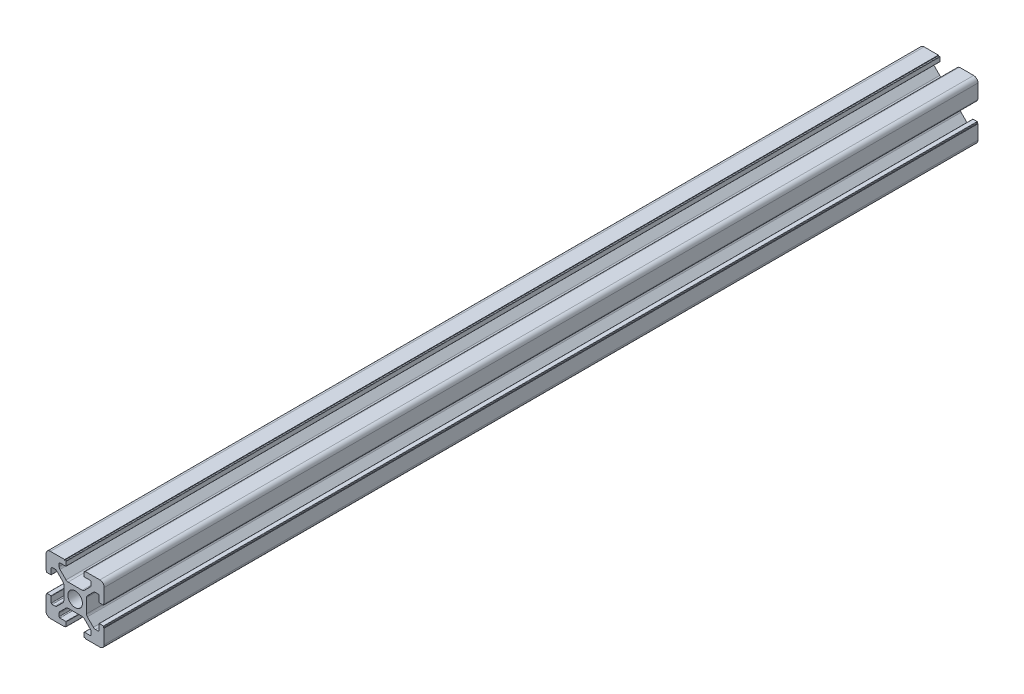
SolidWorks part; units mm, degrees
material "6063-T5"
ref_plane "前视基准面" through (0, 0, 0) normal (0, 0, 1) x (1, 0, 0)
ref_plane "上视基准面" through (0, 0, 0) normal (0, 1, 0) x (1, 0, 0)
ref_plane "右视基准面" through (0, 0, 0) normal (1, 0, 0) x (0, 0, -1)
sketch "草图1" plane through (0, 0, 0) normal (0, 0, 1) x (1, 0, 0)
  line L0 (-1.4389, 10) -> (24.3741, 10) construction
  line L1 (20, 13.6) -> (20, 20)
  line L2 (0, 0) -> (0, 6.4)
  line L3 (0, 20) -> (6.4, 20)
  line L4 (20, 0) -> (20, 6.4)
  line L5 (10, 21.5388) -> (10, -2.4017) construction
  line L6 (6.9, 18.3) -> (6.9, 19.7)
  line L7 (6.8, 18.2) -> (4.8, 18.2)
  line L8 (4.5, 17.9) -> (4.5, 16.9749)
  line L9 (4.7929, 16.2678) -> (6.8678, 14.1929)
  line L10 (7.5749, 13.9) -> (12.4251, 13.9)
  line L11 (6.8, 19.8) -> (6.4, 19.8)
  line L12 (6.4, 19.8) -> (6.4, 20)
  line L13 (0, 13.6) -> (0.2, 13.6)
  line L14 (0.2, 13.6) -> (0.2, 13.2)
  line L15 (0.3, 13.1) -> (1.7, 13.1)
  line L16 (1.8, 13.2) -> (1.8, 15.2)
  line L17 (2.1, 15.5) -> (3.0251, 15.5)
  line L18 (3.7322, 15.2071) -> (5.8071, 13.1322)
  line L19 (6.1, 12.4251) -> (6.1, 7.5749)
  line L20 (13.6, 19.8) -> (13.6, 20)
  line L21 (13.2, 19.8) -> (13.6, 19.8)
  line L22 (13.1, 18.3) -> (13.1, 19.7)
  line L23 (13.2, 18.2) -> (15.2, 18.2)
  line L24 (15.5, 17.9) -> (15.5, 16.9749)
  line L25 (15.2071, 16.2678) -> (13.1322, 14.1929)
  line L26 (0, 6.4) -> (0.2, 6.4)
  line L27 (0.2, 6.4) -> (0.2, 6.8)
  line L28 (0.3, 6.9) -> (1.7, 6.9)
  line L29 (1.8, 6.8) -> (1.8, 4.8)
  line L30 (2.1, 4.5) -> (3.0251, 4.5)
  line L31 (3.7322, 4.7929) -> (5.8071, 6.8678)
  line L32 (13.6, 20) -> (20, 20)
  line L33 (0, 13.6) -> (0, 20)
  line L34 (13.6, 0.2) -> (13.6, 0)
  line L35 (13.2, 0.2) -> (13.6, 0.2)
  line L36 (13.1, 1.7) -> (13.1, 0.3)
  line L37 (13.2, 1.8) -> (15.2, 1.8)
  line L38 (15.5, 2.1) -> (15.5, 3.0251)
  line L39 (15.2071, 3.7322) -> (13.1322, 5.8071)
  line L40 (4.5, 2.1) -> (4.5, 3.0251)
  line L41 (6.8, 1.8) -> (4.8, 1.8)
  line L42 (6.4, 0.2) -> (6.4, 0)
  line L43 (6.8, 0.2) -> (6.4, 0.2)
  line L44 (6.9, 1.7) -> (6.9, 0.3)
  line L45 (4.7929, 3.7322) -> (6.8678, 5.8071)
  line L46 (7.5749, 6.1) -> (12.4251, 6.1)
  line L47 (20, 6.4) -> (19.8, 6.4)
  line L48 (19.8, 6.4) -> (19.8, 6.8)
  line L49 (19.7, 6.9) -> (18.3, 6.9)
  line L50 (18.2, 6.8) -> (18.2, 4.8)
  line L51 (17.9, 4.5) -> (16.9749, 4.5)
  line L52 (16.2678, 4.7929) -> (14.1929, 6.8678)
  line L53 (13.9, 12.4251) -> (13.9, 7.5749)
  line L54 (16.2678, 15.2071) -> (14.1929, 13.1322)
  line L55 (17.9, 15.5) -> (16.9749, 15.5)
  line L56 (18.2, 13.2) -> (18.2, 15.2)
  line L57 (19.7, 13.1) -> (18.3, 13.1)
  line L58 (19.8, 13.6) -> (19.8, 13.2)
  line L59 (20, 13.6) -> (19.8, 13.6)
  line L60 (0, 0) -> (6.4, 0)
  line L61 (13.6, 0) -> (20, 0)
  arc A0 (6.1, 12.4251) -> (5.8071, 13.1322) centre (5.1, 12.4251) ccw
  arc A1 (7.5749, 13.9) -> (6.8678, 14.1929) centre (7.5749, 14.9) cw
  arc A2 (4.5, 16.9749) -> (4.7929, 16.2678) centre (5.5, 16.9749) ccw
  arc A3 (3.7322, 15.2071) -> (3.0251, 15.5) centre (3.0251, 14.5) ccw
  arc A4 (4.5, 17.9) -> (4.8, 18.2) centre (4.8, 17.9) cw
  arc A5 (1.8, 15.2) -> (2.1, 15.5) centre (2.1, 15.2) cw
  arc A6 (0.3, 13.1) -> (0.2, 13.2) centre (0.3, 13.2) cw
  arc A7 (6.9, 19.7) -> (6.8, 19.8) centre (6.8, 19.7) ccw
  arc A8 (1.7, 13.1) -> (1.8, 13.2) centre (1.7, 13.2) ccw
  arc A9 (6.9, 18.3) -> (6.8, 18.2) centre (6.8, 18.3) cw
  arc A10 (13.1, 19.7) -> (13.2, 19.8) centre (13.2, 19.7) cw
  arc A11 (13.1, 18.3) -> (13.2, 18.2) centre (13.2, 18.3) ccw
  arc A12 (15.5, 17.9) -> (15.2, 18.2) centre (15.2, 17.9) ccw
  arc A13 (15.5, 16.9749) -> (15.2071, 16.2678) centre (14.5, 16.9749) cw
  arc A14 (12.4251, 13.9) -> (13.1322, 14.1929) centre (12.4251, 14.9) ccw
  arc A15 (0.3, 6.9) -> (0.2, 6.8) centre (0.3, 6.8) ccw
  arc A16 (1.7, 6.9) -> (1.8, 6.8) centre (1.7, 6.8) cw
  arc A17 (1.8, 4.8) -> (2.1, 4.5) centre (2.1, 4.8) ccw
  arc A18 (3.7322, 4.7929) -> (3.0251, 4.5) centre (3.0251, 5.5) cw
  arc A19 (6.1, 7.5749) -> (5.8071, 6.8678) centre (5.1, 7.5749) cw
  arc A20 (13.1, 0.3) -> (13.2, 0.2) centre (13.2, 0.3) ccw
  arc A21 (13.1, 1.7) -> (13.2, 1.8) centre (13.2, 1.7) cw
  arc A22 (15.5, 2.1) -> (15.2, 1.8) centre (15.2, 2.1) cw
  arc A23 (15.5, 3.0251) -> (15.2071, 3.7322) centre (14.5, 3.0251) ccw
  arc A24 (12.4251, 6.1) -> (13.1322, 5.8071) centre (12.4251, 5.1) cw
  arc A25 (4.5, 2.1) -> (4.8, 1.8) centre (4.8, 2.1) ccw
  arc A26 (6.9, 0.3) -> (6.8, 0.2) centre (6.8, 0.3) cw
  arc A27 (6.9, 1.7) -> (6.8, 1.8) centre (6.8, 1.7) ccw
  arc A28 (4.5, 3.0251) -> (4.7929, 3.7322) centre (5.5, 3.0251) cw
  arc A29 (7.5749, 6.1) -> (6.8678, 5.8071) centre (7.5749, 5.1) ccw
  arc A30 (19.7, 6.9) -> (19.8, 6.8) centre (19.7, 6.8) cw
  arc A31 (18.3, 6.9) -> (18.2, 6.8) centre (18.3, 6.8) ccw
  arc A32 (18.2, 4.8) -> (17.9, 4.5) centre (17.9, 4.8) cw
  arc A33 (16.2678, 4.7929) -> (16.9749, 4.5) centre (16.9749, 5.5) ccw
  arc A34 (13.9, 7.5749) -> (14.1929, 6.8678) centre (14.9, 7.5749) ccw
  arc A35 (13.9, 12.4251) -> (14.1929, 13.1322) centre (14.9, 12.4251) cw
  arc A36 (16.2678, 15.2071) -> (16.9749, 15.5) centre (16.9749, 14.5) cw
  arc A37 (18.2, 15.2) -> (17.9, 15.5) centre (17.9, 15.2) ccw
  arc A38 (18.3, 13.1) -> (18.2, 13.2) centre (18.3, 13.2) cw
  arc A39 (19.7, 13.1) -> (19.8, 13.2) centre (19.7, 13.2) ccw
  circle A40 centre (10, 10) radius 2.5
  point P39 (0.2, 13.1)
  point P42 (6.9, 19.8)
  point P45 (1.8, 13.1)
  point P48 (6.9, 18.2)
  point P66 (10, 13.9)
  point P83 (6.1, 10)
  dimension "D19" = 1
  dimension "D20" = 1
  dimension "D21" = 0.3
  dimension "D22" = 0.1
  dimension "D23" = 5
  dimension "D1" = 20
  dimension "D2" = 20
  dimension "D3" = 10
  dimension "D4" = 10
  dimension "D5" = 1.8
  dimension "D6" = 0.5
  dimension "D7" = 1.6
  dimension "D8" = 3.1
  dimension "D9" = 6.1
  dimension "D10" = 5.5
  dimension "D11" = 3.1
  dimension "D12" = 6.1
  dimension "D13" = 5.5
  dimension "D14" = 1.8
  dimension "D15" = 0.5
  dimension "D16" = 1.5
  dimension "D17" = 45
  dimension "D18" = 1.6
extrude "凸台-拉伸1" add sketch "草图1" along normal blind 300
fillet "圆角1" radius 1.5 4 edges at (20, 0, 150) (0, 0, 150) (0, 20, 150) (20, 20, 150)
